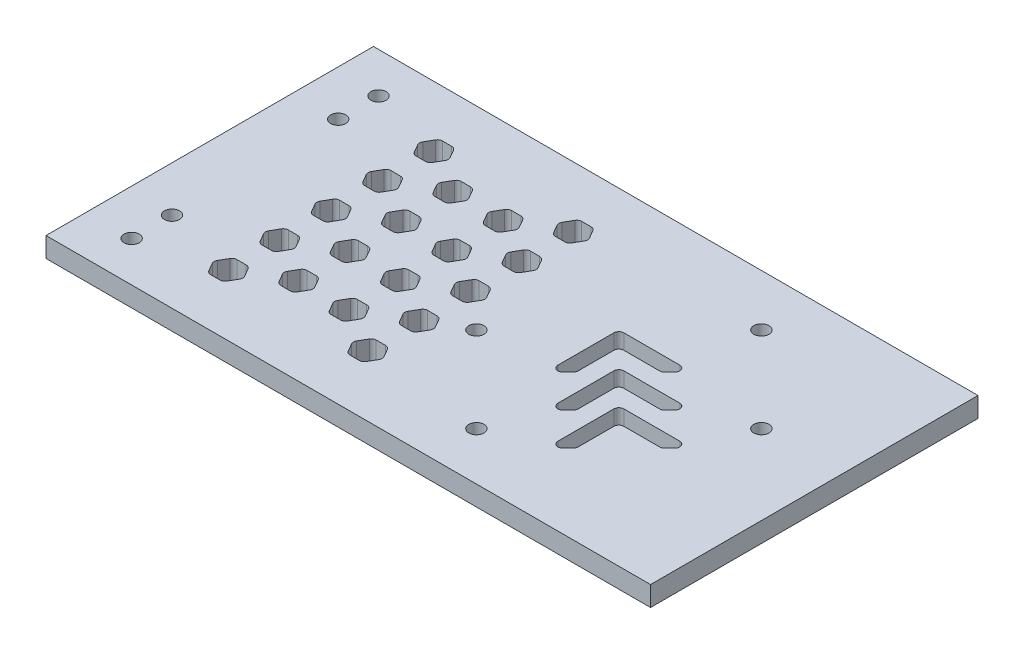
SolidWorks part; units mm, degrees
material "Thornel Mat VMA"
ref_plane "Front Plane" through (0, 0, 0) normal (0, 0, 1) x (1, 0, 0)
ref_plane "Top Plane" through (0, 0, 0) normal (0, 1, 0) x (1, 0, 0)
ref_plane "Right Plane" through (0, 0, 0) normal (1, 0, 0) x (0, 0, -1)
other "Configuration Table"
sketch "草图1" plane through (0, 0, 0) normal (0, 1, 0) x (1, 0, 0)
  line L1 (-60, 32.5) -> (60, 32.5)
  line L2 (-60, 32.5) -> (-60, -32.5)
  line L3 (-60, -32.5) -> (60, -32.5)
  line L4 (60, 32.5) -> (60, -32.5)
  line L5 (-60, 32.5) -> (60, -32.5) construction
  line L6 (-60, -32.5) -> (60, 32.5) construction
  point P0 (0, 0)
  dimension "D1" = 65
  dimension "D2" = 120
extrude "凸台-拉伸1" add sketch "草图1" along normal blind 3.95
sketch "草图2" plane through (0, 3.95, 0) normal (0, 1, 0) x (1, 0, 0)
  line L0 (-21.5, 21.5) -> (13.2745, -13.2745) construction
  line L1 (-60, 32.5) -> (-60, -32.5) construction
  dimension "D1" = 45
sketch "草图4" plane through (0, 3.95, 0) normal (0, 1, 0) x (1, 0, 0)
  line L0 (27.23, 22.2674) -> (-1.0542, -6.0168) construction
  line L1 (-141442.8562, 141442.8562) -> (141434.6307, -141434.6307) construction
  line L2 (15.9163, -22.9874) -> (-1.0542, -6.0168) construction
  line L3 (27.23, 22.2674) -> (44.2006, 5.2969) construction
  circle A0 centre (-1.0542, -6.0168) radius 1.5
  circle A1 centre (27.23, 22.2674) radius 1.5
  circle A2 centre (15.9163, -22.9874) radius 1.5
  circle A3 centre (44.2006, 5.2969) radius 1.5
  dimension "D4" = 3
  dimension "D1" = 40
  dimension "D2" = 24
  dimension "D3" = 24
  dimension "D5" = 5
extrude "切除-拉伸1" cut sketch "草图4" against normal blind 4
sketch "草图5" plane through (0, 3.95, 0) normal (0, 1, 0) x (1, 0, 0)
  line L0 (27.23, 22.2674) -> (-1.0542, -6.0168) construction
  line L1 (13.0879, 8.1253) -> (28.4989, -7.2857) construction
  line L2 (13.0879, 8.1253) -> (13.0879, -6.3747)
  line L3 (13.0879, -6.3747) -> (16.0879, -3.3747)
  line L4 (16.0879, -3.3747) -> (16.0879, 5.1253)
  line L5 (16.0879, 5.1253) -> (24.5879, 5.1253)
  line L6 (24.5879, 5.1253) -> (27.5879, 8.1253)
  line L7 (27.5879, 8.1253) -> (13.0879, 8.1253)
  line L8 (34.1234, 1.5898) -> (19.6234, 1.5898)
  line L9 (19.6234, 1.5898) -> (19.6234, -12.9102)
  line L10 (19.6234, -12.9102) -> (22.6234, -9.9102)
  line L11 (22.6234, -9.9102) -> (22.6234, -1.4102)
  line L12 (22.6234, -1.4102) -> (31.1234, -1.4102)
  line L13 (31.1234, -1.4102) -> (34.1234, 1.5898)
  line L14 (40.659, -4.9458) -> (26.159, -4.9458)
  line L15 (26.159, -4.9458) -> (26.159, -19.4458)
  line L16 (26.159, -19.4458) -> (29.159, -16.4458)
  line L17 (29.159, -16.4458) -> (29.159, -7.9458)
  line L18 (29.159, -7.9458) -> (37.659, -7.9458)
  line L19 (37.659, -7.9458) -> (40.659, -4.9458)
  point P15 (13.0879, 8.1253)
  dimension "D1" = 3
  dimension "D2" = 3
  dimension "D4" = 90
  dimension "D5" = 5
  dimension "D6" = 14.5
  dimension "D3" = 3
extrude "切除-拉伸2" cut sketch "草图5" against normal blind 8
sketch "草图6" plane through (0, 3.95, 0) normal (0, 1, 0) x (1, 0, 0)
  line L0 (-55, -32.5) -> (-55, 56.0414) construction
  line L2 (-60, 32.5) -> (-60, -32.5) construction
  dimension "D1" = 5
sketch "草图7" plane through (0, 3.95, 0) normal (0, 1, 0) x (1, 0, 0)
  line L0 (-55, -200032.5) -> (-55, 200056.0414) construction
  line L1 (-60, -32.5) -> (60, -32.5) construction
  line L2 (-30, 0) -> (53.9878, 0) construction
  circle A0 centre (-51, -24.5) radius 1.5
  circle A1 centre (-51, -16.5) radius 1.5
  circle A2 centre (-51, 24.5) radius 1.5
  circle A3 centre (-51, 16.5) radius 1.5
  dimension "D2" = 3
  dimension "D3" = 3
  dimension "D1" = 4
  dimension "D4" = 8
  dimension "D5" = 8
extrude "切除-拉伸3" cut sketch "草图7" against normal blind 8
sketch "草图9" plane through (0, 3.95, 0) normal (0, 1, 0) x (1, 0, 0)
  line L0 (60, 32.5) -> (-60, 32.5) construction
  line L1 (-34.5, 17.9019) -> (-33, 20.5)
  line L2 (-33, 20.5) -> (-34.5, 23.0981)
  line L3 (-34.5, 23.0981) -> (-37.5, 23.0981)
  line L4 (-37.5, 23.0981) -> (-39, 20.5)
  line L5 (-39, 20.5) -> (-37.5, 17.9019)
  line L6 (-37.5, 17.9019) -> (-34.5, 17.9019)
  line L7 (-60, 32.5) -> (-60, -32.5) construction
  line L8 (-34.5, 7.7058) -> (-33, 10.3038)
  line L9 (-33, 10.3038) -> (-34.5, 12.9019)
  line L10 (-34.5, 12.9019) -> (-37.5, 12.9019)
  line L11 (-37.5, 12.9019) -> (-39, 10.3038)
  line L12 (-39, 10.3038) -> (-37.5, 7.7058)
  line L13 (-37.5, 7.7058) -> (-34.5, 7.7058)
  line L14 (-34.5, -2.4904) -> (-33, 0.1077)
  line L15 (-33, 0.1077) -> (-34.5, 2.7058)
  line L16 (-34.5, 2.7058) -> (-37.5, 2.7058)
  line L17 (-37.5, 2.7058) -> (-39, 0.1077)
  line L18 (-39, 0.1077) -> (-37.5, -2.4904)
  line L19 (-37.5, -2.4904) -> (-34.5, -2.4904)
  line L20 (-34.5, -12.6865) -> (-33, -10.0885)
  line L21 (-33, -10.0885) -> (-34.5, -7.4904)
  line L22 (-34.5, -7.4904) -> (-37.5, -7.4904)
  line L23 (-37.5, -7.4904) -> (-39, -10.0885)
  line L24 (-39, -10.0885) -> (-37.5, -12.6865)
  line L25 (-37.5, -12.6865) -> (-34.5, -12.6865)
  line L26 (-34.5, -22.8827) -> (-33, -20.2846)
  line L27 (-33, -20.2846) -> (-34.5, -17.6865)
  line L28 (-34.5, -17.6865) -> (-37.5, -17.6865)
  line L29 (-37.5, -17.6865) -> (-39, -20.2846)
  line L30 (-39, -20.2846) -> (-37.5, -22.8827)
  line L31 (-37.5, -22.8827) -> (-34.5, -22.8827)
  line L32 (-36, 20.5) -> (-31.5, 17.9019) construction
  line L33 (-24.1699, 15.4019) -> (-25.6699, 18)
  line L34 (-25.6699, 18) -> (-28.6699, 18)
  line L35 (-28.6699, 18) -> (-30.1699, 15.4019)
  line L36 (-30.1699, 15.4019) -> (-28.6699, 12.8038)
  line L37 (-28.6699, 12.8038) -> (-25.6699, 12.8038)
  line L38 (-25.6699, 12.8038) -> (-24.1699, 15.4019)
  line L39 (-36, 17.9019) -> (-36, 12.9019) construction
  line L40 (-24.1699, 5.2058) -> (-25.6699, 7.8038)
  line L41 (-25.6699, 7.8038) -> (-28.6699, 7.8038)
  line L42 (-28.6699, 7.8038) -> (-30.1699, 5.2058)
  line L43 (-30.1699, 5.2058) -> (-28.6699, 2.6077)
  line L44 (-28.6699, 2.6077) -> (-25.6699, 2.6077)
  line L45 (-25.6699, 2.6077) -> (-24.1699, 5.2058)
  line L46 (-24.1699, -4.9904) -> (-25.6699, -2.3923)
  line L47 (-25.6699, -2.3923) -> (-28.6699, -2.3923)
  line L48 (-28.6699, -2.3923) -> (-30.1699, -4.9904)
  line L49 (-30.1699, -4.9904) -> (-28.6699, -7.5885)
  line L50 (-28.6699, -7.5885) -> (-25.6699, -7.5885)
  line L51 (-25.6699, -7.5885) -> (-24.1699, -4.9904)
  line L52 (-24.1699, -15.1865) -> (-25.6699, -12.5885)
  line L53 (-25.6699, -12.5885) -> (-28.6699, -12.5885)
  line L54 (-28.6699, -12.5885) -> (-30.1699, -15.1865)
  line L55 (-30.1699, -15.1865) -> (-28.6699, -17.7846)
  line L56 (-28.6699, -17.7846) -> (-25.6699, -17.7846)
  line L57 (-25.6699, -17.7846) -> (-24.1699, -15.1865)
  line L58 (-22.1699, 32.5) -> (-22.1699, -33.0715) construction
  line L59 (-8.3397, 17.9019) -> (-8.3397, 12.9019) construction
  line L60 (-18.6699, -17.7846) -> (-20.1699, -15.1865)
  line L61 (-15.6699, -17.7846) -> (-18.6699, -17.7846)
  line L62 (-14.1699, -15.1865) -> (-15.6699, -17.7846)
  line L63 (-15.6699, -12.5885) -> (-14.1699, -15.1865)
  line L64 (-18.6699, -12.5885) -> (-15.6699, -12.5885)
  line L65 (-20.1699, -15.1865) -> (-18.6699, -12.5885)
  line L66 (-18.6699, -7.5885) -> (-20.1699, -4.9904)
  line L67 (-15.6699, -7.5885) -> (-18.6699, -7.5885)
  line L68 (-14.1699, -4.9904) -> (-15.6699, -7.5885)
  line L69 (-15.6699, -2.3923) -> (-14.1699, -4.9904)
  line L70 (-18.6699, -2.3923) -> (-15.6699, -2.3923)
  line L71 (-20.1699, -4.9904) -> (-18.6699, -2.3923)
  line L72 (-18.6699, 2.6077) -> (-20.1699, 5.2058)
  line L73 (-15.6699, 2.6077) -> (-18.6699, 2.6077)
  line L74 (-14.1699, 5.2058) -> (-15.6699, 2.6077)
  line L75 (-15.6699, 7.8038) -> (-14.1699, 5.2058)
  line L76 (-18.6699, 7.8038) -> (-15.6699, 7.8038)
  line L77 (-20.1699, 5.2058) -> (-18.6699, 7.8038)
  line L78 (-18.6699, 12.8038) -> (-20.1699, 15.4019)
  line L79 (-15.6699, 12.8038) -> (-18.6699, 12.8038)
  line L80 (-14.1699, 15.4019) -> (-15.6699, 12.8038)
  line L81 (-15.6699, 18) -> (-14.1699, 15.4019)
  line L82 (-18.6699, 18) -> (-15.6699, 18)
  line L83 (-20.1699, 15.4019) -> (-18.6699, 18)
  line L84 (-6.8397, -22.8827) -> (-9.8397, -22.8827)
  line L85 (-5.3397, -20.2846) -> (-6.8397, -22.8827)
  line L86 (-6.8397, -17.6865) -> (-5.3397, -20.2846)
  line L87 (-9.8397, -17.6865) -> (-6.8397, -17.6865)
  line L88 (-11.3397, -20.2846) -> (-9.8397, -17.6865)
  line L89 (-9.8397, -22.8827) -> (-11.3397, -20.2846)
  line L90 (-6.8397, -12.6865) -> (-9.8397, -12.6865)
  line L91 (-5.3397, -10.0885) -> (-6.8397, -12.6865)
  line L92 (-6.8397, -7.4904) -> (-5.3397, -10.0885)
  line L93 (-9.8397, -7.4904) -> (-6.8397, -7.4904)
  line L94 (-11.3397, -10.0885) -> (-9.8397, -7.4904)
  line L95 (-9.8397, -12.6865) -> (-11.3397, -10.0885)
  line L96 (-6.8397, -2.4904) -> (-9.8397, -2.4904)
  line L97 (-5.3397, 0.1077) -> (-6.8397, -2.4904)
  line L98 (-6.8397, 2.7058) -> (-5.3397, 0.1077)
  line L99 (-9.8397, 2.7058) -> (-6.8397, 2.7058)
  line L100 (-11.3397, 0.1077) -> (-9.8397, 2.7058)
  line L101 (-9.8397, -2.4904) -> (-11.3397, 0.1077)
  line L102 (-6.8397, 7.7058) -> (-9.8397, 7.7058)
  line L103 (-5.3397, 10.3038) -> (-6.8397, 7.7058)
  line L104 (-6.8397, 12.9019) -> (-5.3397, 10.3038)
  line L105 (-9.8397, 12.9019) -> (-6.8397, 12.9019)
  line L106 (-11.3397, 10.3038) -> (-9.8397, 12.9019)
  line L107 (-9.8397, 7.7058) -> (-11.3397, 10.3038)
  line L108 (-6.8397, 17.9019) -> (-9.8397, 17.9019)
  line L109 (-5.3397, 20.5) -> (-6.8397, 17.9019)
  line L110 (-6.8397, 23.0981) -> (-5.3397, 20.5)
  line L111 (-9.8397, 23.0981) -> (-6.8397, 23.0981)
  line L112 (-11.3397, 20.5) -> (-9.8397, 23.0981)
  line L113 (-9.8397, 17.9019) -> (-11.3397, 20.5)
  circle A0 centre (-36, 20.5) radius 2.5981 construction
  circle A1 centre (-27.1699, 15.4019) radius 2.5981 construction
  circle A2 centre (-17.1699, 15.4019) radius 2.5981 construction
  circle A3 centre (-8.3397, 20.5) radius 2.5981 construction
  point P14 (-36, 15.4019)
  dimension "D1" = 3
  dimension "D2" = 12
  dimension "D3" = 24
  dimension "D5" = 5
  dimension "D6" = 3
  dimension "D8" = 5
  dimension "D9" = 5
  dimension "D4" = 5
  dimension "D7" = 4
extrude "切除-拉伸4" cut sketch "草图9" against normal blind 10
fillet "圆角1" radius 1 126 edges at (24.5879, 1.975, -5.1253) (16.0879, 1.975, -5.1253) (16.0879, 1.975, 3.3747) (13.0879, 1.975, 6.3747) (13.0879, 1.975, -8.1253) (27.5879, 1.975, -8.1253) (40.659, 1.975, 4.9458) (37.659, 1.975, 7.9458) (29.159, 1.975, 7.9458) (29.159, 1.975, 16.4458) (26.159, 1.975, 19.4458) (26.159, 1.975, 4.9458) (34.1234, 1.975, -1.5898) (31.1234, 1.975, 1.4102) (22.6234, 1.975, 1.4102) (22.6234, 1.975, 9.9102) (19.6234, 1.975, 12.9102) (19.6234, 1.975, -1.5898) (-39, 1.975, -20.5) (-34.5, 1.975, -23.0981) (-33, 1.975, -20.5) (-34.5, 1.975, -17.9019) (-37.5, 1.975, -17.9019) (-9.8397, 1.975, -17.9019) (-11.3397, 1.975, -20.5) (-9.8397, 1.975, -23.0981) (-6.8397, 1.975, -23.0981) (-5.3397, 1.975, -20.5) (-6.8397, 1.975, -17.9019) (-9.8397, 1.975, -7.7058) (-11.3397, 1.975, -10.3038) (-9.8397, 1.975, -12.9019) (-6.8397, 1.975, -12.9019) (-5.3397, 1.975, -10.3038) (-6.8397, 1.975, -7.7058) (-9.8397, 1.975, 2.4904) (-11.3397, 1.975, -0.1077) (-9.8397, 1.975, -2.7058) (-6.8397, 1.975, -2.7058) (-5.3397, 1.975, -0.1077) (-6.8397, 1.975, 2.4904) (-9.8397, 1.975, 12.6865) (-11.3397, 1.975, 10.0885) (-9.8397, 1.975, 7.4904) (-6.8397, 1.975, 7.4904) (-5.3397, 1.975, 10.0885) (-6.8397, 1.975, 12.6865) (-9.8397, 1.975, 22.8827) (-11.3397, 1.975, 20.2846) (-9.8397, 1.975, 17.6865) (-6.8397, 1.975, 17.6865) (-5.3397, 1.975, 20.2846) (-6.8397, 1.975, 22.8827) (-20.1699, 1.975, -15.4019) (-18.6699, 1.975, -18) (-15.6699, 1.975, -18) (-14.1699, 1.975, -15.4019) (-15.6699, 1.975, -12.8038) (-18.6699, 1.975, -12.8038) (-20.1699, 1.975, -5.2058) (-18.6699, 1.975, -7.8038) (-15.6699, 1.975, -7.8038) (-14.1699, 1.975, -5.2058) (-15.6699, 1.975, -2.6077) (-18.6699, 1.975, -2.6077) (-20.1699, 1.975, 4.9904) (-18.6699, 1.975, 2.3923) (-15.6699, 1.975, 2.3923) (-14.1699, 1.975, 4.9904) (-15.6699, 1.975, 7.5885) (-18.6699, 1.975, 7.5885) (-20.1699, 1.975, 15.1865) (-18.6699, 1.975, 12.5885) (-15.6699, 1.975, 12.5885) (-14.1699, 1.975, 15.1865) (-15.6699, 1.975, 17.7846) (-18.6699, 1.975, 17.7846) (-28.6699, 1.975, 17.7846) (-30.1699, 1.975, 15.1865) (-28.6699, 1.975, 12.5885) (-25.6699, 1.975, 12.5885) (-24.1699, 1.975, 15.1865) (-25.6699, 1.975, 17.7846) (-28.6699, 1.975, 7.5885) (-30.1699, 1.975, 4.9904) (-28.6699, 1.975, 2.3923) (-25.6699, 1.975, 2.3923) (-24.1699, 1.975, 4.9904) (-25.6699, 1.975, 7.5885) (-28.6699, 1.975, -2.6077) (-30.1699, 1.975, -5.2058) (-28.6699, 1.975, -7.8038) (-25.6699, 1.975, -7.8038) (-24.1699, 1.975, -5.2058) (-25.6699, 1.975, -2.6077) (-28.6699, 1.975, -12.8038) (-30.1699, 1.975, -15.4019) (-28.6699, 1.975, -18) (-25.6699, 1.975, -18) (-24.1699, 1.975, -15.4019) (-25.6699, 1.975, -12.8038) (-39, 1.975, 20.2846) (-37.5, 1.975, 17.6865) (-34.5, 1.975, 17.6865) (-33, 1.975, 20.2846) (-34.5, 1.975, 22.8827) (-37.5, 1.975, 22.8827) (-39, 1.975, 10.0885) (-37.5, 1.975, 7.4904) (-34.5, 1.975, 7.4904) (-33, 1.975, 10.0885) (-34.5, 1.975, 12.6865) (-37.5, 1.975, 12.6865) (-39, 1.975, -0.1077) (-37.5, 1.975, -2.7058) (-34.5, 1.975, -2.7058) (-33, 1.975, -0.1077) (-34.5, 1.975, 2.4904) (-37.5, 1.975, 2.4904) (-39, 1.975, -10.3038) (-37.5, 1.975, -12.9019) (-34.5, 1.975, -12.9019) (-33, 1.975, -10.3038) (-34.5, 1.975, -7.7058) (-37.5, 1.975, -7.7058) (-37.5, 1.975, -23.0981)
